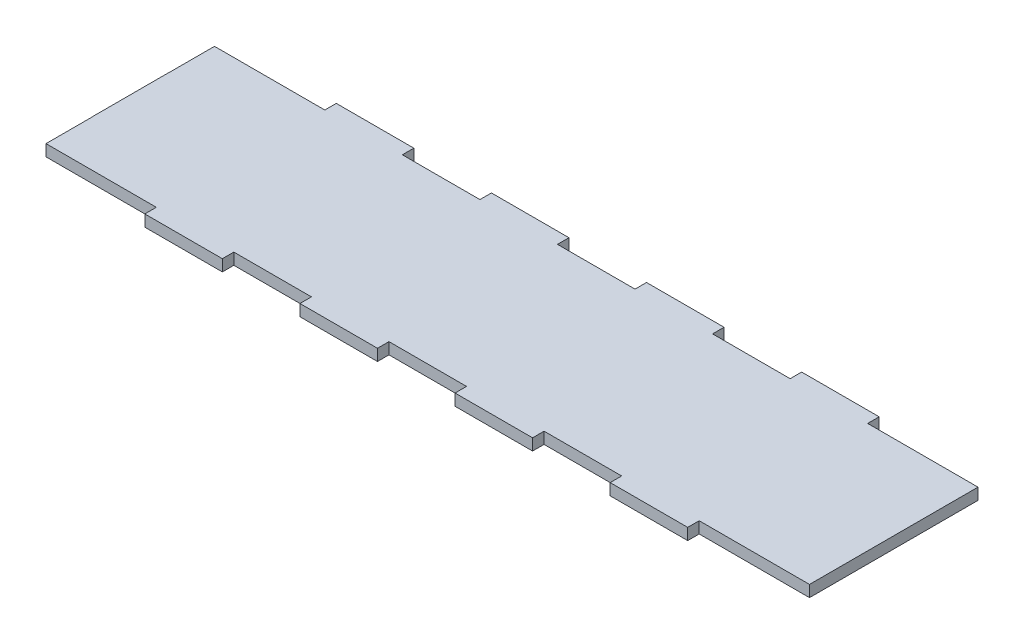
SolidWorks part; units mm, degrees
ref_plane "Front Plane" through (0, 0, 0) normal (0, 0, 1) x (1, 0, 0)
ref_plane "Top Plane" through (0, 0, 0) normal (0, 1, 0) x (1, 0, 0)
ref_plane "Right Plane" through (0, 0, 0) normal (1, 0, 0) x (0, 0, -1)
sketch "Sketch1" plane through (0, 0, 0) normal (0, 1, 0) x (1, 0, 0)
  line L1 (262.6998, 188.938) -> (-262.6998, 188.938)
  line L2 (262.6998, 188.938) -> (262.6998, -188.938)
  line L3 (262.6998, -188.938) -> (-262.6998, -188.938)
  line L4 (-262.6998, 188.938) -> (-262.6998, -188.938)
  line L5 (262.6998, 188.938) -> (-262.6998, -188.938) construction
  line L6 (262.6998, -188.938) -> (-262.6998, 188.938) construction
  point P0 (0, 0)
extrude "Boss-Extrude1" add sketch "Sketch1" along normal blind 6
sketch "Sketch2" plane through (0, 6, 0) normal (0, 1, 0) x (1, 0, 0)
  line B0 (-187.3458, 75.5869) -> (-187.3458, 51.8369)
  line B1 (-187.3458, 51.8369) -> (-187.4064, 51.8369)
  line B2 (-187.4064, 51.8369) -> (-187.4064, 11.3369)
  line B3 (-187.4064, 11.3369) -> (-187.3458, 11.3369)
  line B4 (-187.3458, 11.3369) -> (-187.3458, -12.4131)
  line B5 (-187.3458, -12.4131) -> (-129.7408, -12.4131)
  line B6 (-129.7408, -12.4131) -> (-129.7408, -18.4131)
  line B7 (-129.7408, -18.4131) -> (-89.2408, -18.4131)
  line B8 (-89.2408, -18.4131) -> (-89.2408, -12.4131)
  line B9 (-89.2408, -12.4131) -> (-48.7408, -12.4131)
  line B10 (-48.7408, -12.4131) -> (-48.7408, -18.4131)
  line B11 (-48.7408, -18.4131) -> (-8.2408, -18.4131)
  line B12 (-8.2408, -18.4131) -> (-8.2408, -12.4131)
  line B13 (-8.2408, -12.4131) -> (32.2592, -12.4131)
  line B14 (32.2592, -12.4131) -> (32.2592, -18.4131)
  line B15 (32.2592, -18.4131) -> (72.7592, -18.4131)
  line B16 (72.7592, -18.4131) -> (72.7592, -12.4131)
  line B17 (72.7592, -12.4131) -> (113.2592, -12.4131)
  line B18 (113.2592, -12.4131) -> (113.2592, -18.4131)
  line B19 (113.2592, -18.4131) -> (153.7592, -18.4131)
  line B20 (153.7592, -18.4131) -> (153.7592, -12.4131)
  line B21 (153.7592, -12.4131) -> (194.2592, -12.4131)
  line B22 (194.2592, -12.4131) -> (211.3642, -12.4131)
  line B23 (211.3642, -12.4131) -> (211.3642, 11.3369)
  line B24 (211.3642, 11.3369) -> (211.3642, 51.8369)
  line B25 (211.3642, 51.8369) -> (211.3642, 75.5869)
  line B26 (211.3642, 75.5869) -> (153.7592, 75.5869)
  line B27 (153.7592, 75.5869) -> (153.7592, 81.5869)
  line B28 (153.7592, 81.5869) -> (113.2592, 81.5869)
  line B29 (113.2592, 81.5869) -> (113.2592, 75.5869)
  line B30 (113.2592, 75.5869) -> (72.7592, 75.5869)
  line B31 (72.7592, 75.5869) -> (72.7592, 81.5869)
  line B32 (72.7592, 81.5869) -> (32.2592, 81.5869)
  line B33 (32.2592, 81.5869) -> (32.2592, 75.5869)
  line B34 (32.2592, 75.5869) -> (-8.2408, 75.5869)
  line B35 (-8.2408, 75.5869) -> (-8.2408, 81.5869)
  line B36 (-8.2408, 81.5869) -> (-48.7408, 81.5869)
  line B37 (-48.7408, 81.5869) -> (-48.7408, 75.5869)
  line B38 (-48.7408, 75.5869) -> (-89.2408, 75.5869)
  line B39 (-89.2408, 75.5869) -> (-89.2408, 81.5869)
  line B40 (-89.2408, 81.5869) -> (-129.7408, 81.5869)
  line B41 (-129.7408, 81.5869) -> (-129.7408, 75.5869)
  line B42 (-129.7408, 75.5869) -> (-170.2408, 75.5869)
  line B43 (-170.2408, 75.5869) -> (-187.3458, 75.5869)
sketch_block_instance "Block1-2"
sketch_block "Block1"
extrude "Cut-Extrude-Thin2" cut sketch "Sketch2" against normal through all thin thin type mid plane wall 0.01
